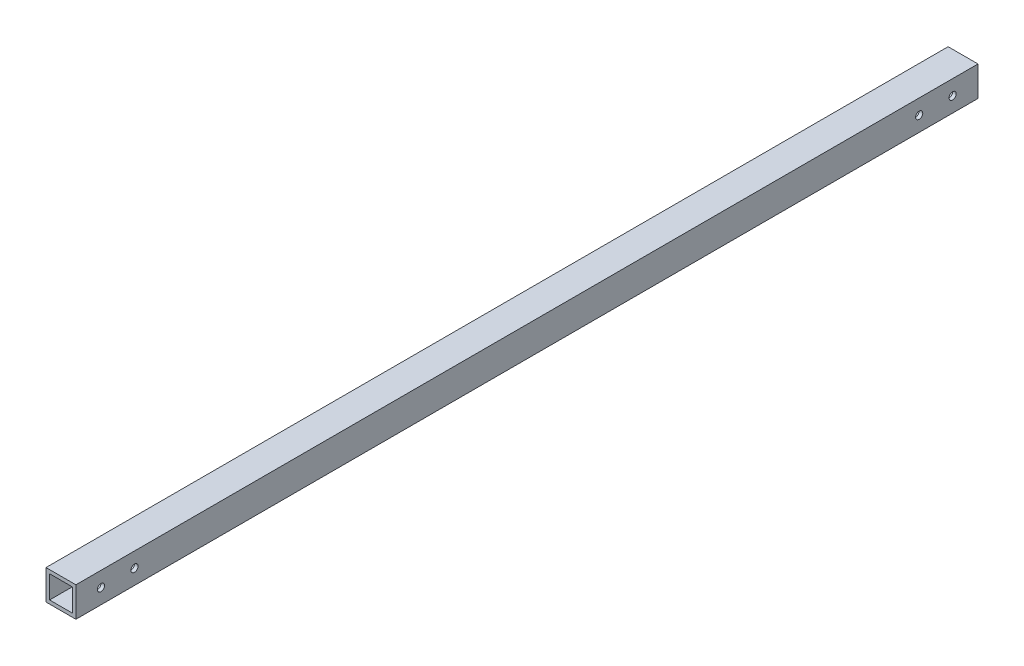
SolidWorks part; units mm, degrees
ref_plane "前视基准面" through (0, 0, 0) normal (0, 0, 1) x (1, 0, 0)
ref_plane "上视基准面" through (0, 0, 0) normal (0, 1, 0) x (1, 0, 0)
ref_plane "右视基准面" through (0, 0, 0) normal (1, 0, 0) x (0, 0, -1)
sketch "草图1" plane through (0, 0, 0) normal (0, 0, 1) x (1, 0, 0)
  line L1 (0, 0) -> (25, 0)
  line L2 (0, 0) -> (0, -25)
  line L3 (0, -25) -> (25, -25)
  line L4 (25, 0) -> (25, -25)
  line L5 (3, -3) -> (22, -3)
  line L6 (3, -3) -> (3, -22)
  line L7 (3, -22) -> (22, -22)
  line L8 (22, -3) -> (22, -22)
  dimension "D1" = 3
  dimension "D2" = 3
  dimension "D3" = 3
  dimension "D4" = 3
  dimension "D5" = 25
  dimension "D6" = 25
extrude "拉伸1" add sketch "草图1" along normal blind 754.5
hole_wizard "Ø6.0 (6) 直径孔1" positions "草图3" profile "草图4" hole size "Ø6.0" standard "GB" end condition through all
sketch "草图3" plane through (25, 0, 0) normal (1, 0, 0) x (0, 0, -1)
  line L1 (-754.5, -25) -> (0, -25) construction
  line L2 (-754.5, -25) -> (-754.5, 0) construction
  point P1 (-705.5, -12.5)
  point P3 (-733.5, -12.5)
  dimension "D1" = 21
  dimension "D2" = 28
  dimension "D3" = 12.5
sketch "草图4" plane through (25, -12.5, 705.5) normal (0, 1, 0) x (0, 0, -1)
  line L0 (0, 0) -> (0, 25)
  line L1 (0, 25) -> (3, 25)
  line L2 (3, 25) -> (3, 0)
  line L5 (3, 0) -> (0, 0)
  line L11 (0, -6.35) -> (0, 107.95) construction
  dimension "通孔孔直径" = 6
  dimension "通孔孔深度" = 25
sketch "草图5" plane through (0, 0, 0) normal (-1, 0, 0) x (0, 0, 1)
  circle A0 centre (705.5, -12.5) radius 6
  circle A1 centre (733.5, -12.5) radius 6
  circle A2 centre (705.5, -12.5) radius 3 construction
  dimension "D1" = 12
  dimension "D2" = 12
extrude "切除-拉伸1" cut sketch "草图5" against normal up to next
pattern_linear "阵列(线性)1" count 2 spacing 684.3 along (0, 0, -1) of "Ø6.0 (6) 直径孔1", "切除-拉伸1"
